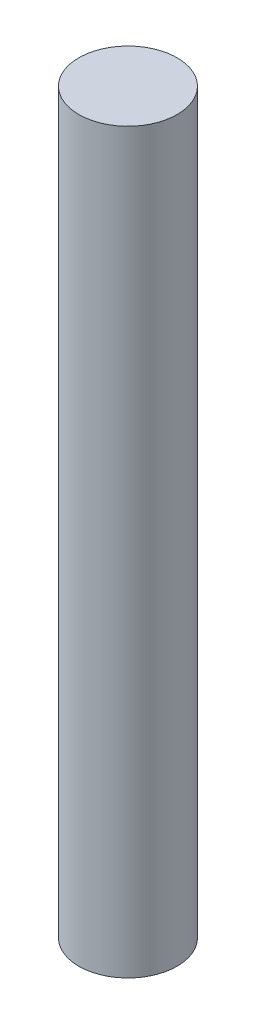
SolidWorks part; units mm, degrees
ref_plane "Front Plane" through (0, 0, 0) normal (0, 0, 1) x (1, 0, 0)
ref_plane "Top Plane" through (0, 0, 0) normal (0, 1, 0) x (1, 0, 0)
ref_plane "Right Plane" through (0, 0, 0) normal (1, 0, 0) x (0, 0, -1)
sketch "Sketch1" plane through (0, 0, 0) normal (0, 1, 0) x (1, 0, 0)
  circle A0 centre (0, 0) radius 2.5
extrude "Boss-Extrude1" add sketch "Sketch1" along normal blind 37.5
sketch "Sketch2" plane through (0, 37.5, 0) normal (0, 1, 0) x (1, 0, 0)
  point P0 (0, 0)
